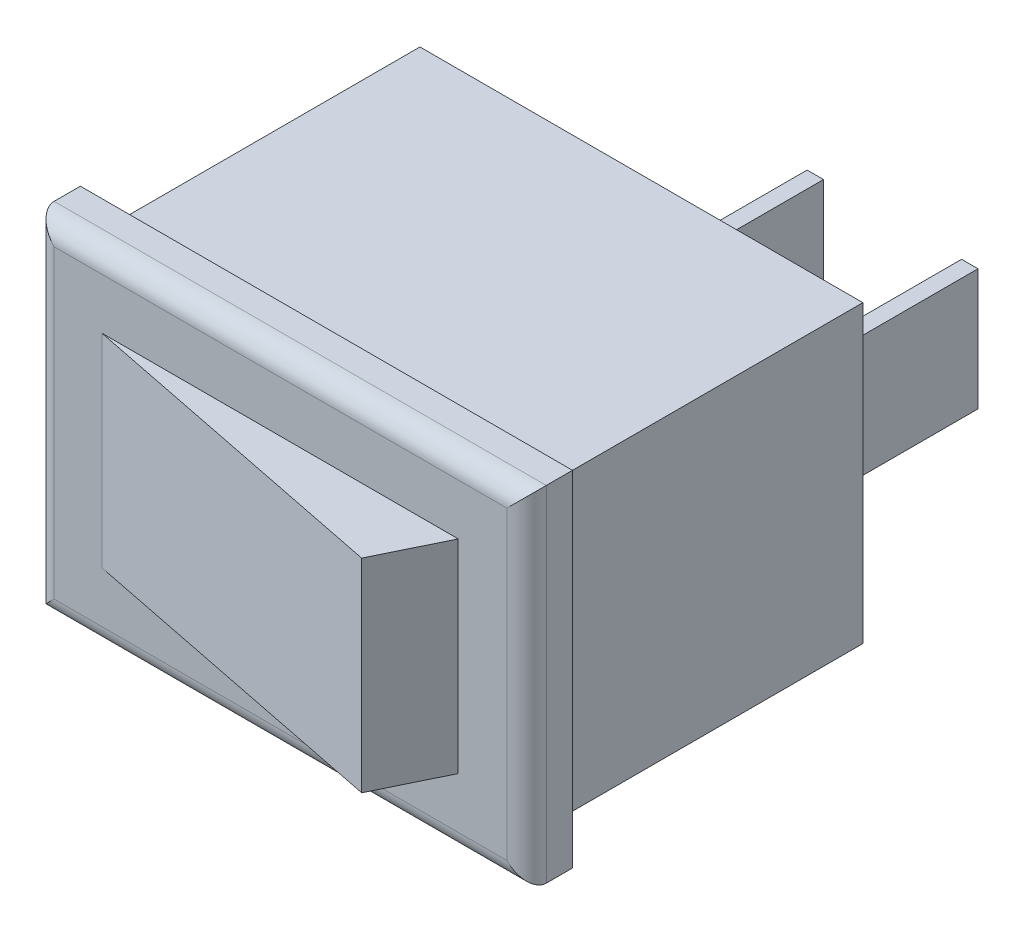
SolidWorks part; units mm, degrees
ref_plane "前视基准面" through (0, 0, 0) normal (0, 0, 1) x (1, 0, 0)
ref_plane "上视基准面" through (0, 0, 0) normal (0, 1, 0) x (1, 0, 0)
ref_plane "右视基准面" through (0, 0, 0) normal (1, 0, 0) x (0, 0, -1)
other "Configuration Table"
ref_plane "基准面1" through (0, 0, 11) normal (0, 0, 1) x (1, 0, 0)
sketch "草图1" plane through (0, 0, 11) normal (0, 0, 1) x (1, 0, 0)
  line L0 (-7.5, 5.25) -> (-7.5, -5.25)
  line L1 (-7.5, -5.25) -> (7.5, -5.25)
  line L2 (7.5, -5.25) -> (7.5, 5.25)
  line L3 (7.5, 5.25) -> (-7.5, 5.25)
extrude "凸台-拉伸1" add sketch "草图1" against normal blind 1.4
ref_plane "基准面2" through (0, -3.0974, 0) normal (0, -1, 0) x (1, 0, 0)
sketch "草图2" plane through (0, -3.0974, 0) normal (0, -1, 0) x (1, 0, 0)
  line L0 (5.4168, 11) -> (5.4168, 13.1716)
  line L1 (5.4168, 13.1716) -> (-5.4413, 11)
  line L2 (-5.4413, 11) -> (5.4168, 11)
extrude "凸台-拉伸2" add sketch "草图2" against normal blind 6.1948
sketch "草图3" plane through (0, 0, 9.6) normal (0, 0, -1) x (-1, 0, 0)
  line L0 (-6.75, -4.5) -> (-6.75, 4.5)
  line L1 (-6.75, 4.5) -> (6.75, 4.5)
  line L2 (6.75, 4.5) -> (6.75, -4.5)
  line L3 (6.75, -4.5) -> (-6.75, -4.5)
extrude "凸台-拉伸3" add sketch "草图3" along normal blind 9.6
sketch "草图4" plane through (0, 0, 0) normal (0, 0, -1) x (-1, 0, 0)
  line L0 (0.9153, 2.5) -> (0.9153, -2.5)
  line L1 (0.9153, -2.5) -> (-0.9153, -2.5)
  line L2 (-0.9153, -2.5) -> (-0.9153, 2.5)
  line L3 (-0.9153, 2.5) -> (0.9153, 2.5)
extrude "凸台-拉伸4" add sketch "草图4" along normal blind 0.3
sketch "草图5" plane through (0, 0, -0.3) normal (0, 0, -1) x (-1, 0, 0)
  line L0 (0.25, 1.85) -> (0.25, -1.85)
  line L1 (0.25, -1.85) -> (-0.25, -1.85)
  line L2 (-0.25, -1.85) -> (-0.25, 1.85)
  line L3 (-0.25, 1.85) -> (0.25, 1.85)
extrude "凸台-拉伸5" add sketch "草图5" along normal blind 5
sketch "草图6" plane through (0, 0, 0) normal (0, 0, -1) x (-1, 0, 0)
  line L0 (-3.7945, 2.5) -> (-3.7945, -2.5)
  line L1 (-3.7945, -2.5) -> (-5.625, -2.5)
  line L2 (-5.625, -2.5) -> (-5.625, 2.5)
  line L3 (-5.625, 2.5) -> (-3.7945, 2.5)
extrude "凸台-拉伸6" add sketch "草图6" along normal blind 0.3
sketch "草图7" plane through (0, 0, -0.3) normal (0, 0, -1) x (-1, 0, 0)
  line L0 (-4.9598, 1.85) -> (-4.4598, 1.85)
  line L1 (-4.4598, 1.85) -> (-4.4598, -1.85)
  line L2 (-4.4598, -1.85) -> (-4.9598, -1.85)
  line L3 (-4.9598, -1.85) -> (-4.9598, 1.85)
extrude "凸台-拉伸7" add sketch "草图7" along normal blind 5
draft "拔模1" type of draft neutral plane draft angle 26 faces to draft 1 face at (5.4168, 0, 12.0858) neutral plane through (0, 0, 11) neutral plane normal (0, 0, 1) parameters "D1"=26
fillet "圆角1" radius 0.6 4 edges at (7.5, 0, 11) (0, 5.25, 11) (0, -5.25, 11) (-7.5, 0, 11)
sketch "草图8" [suppressed] plane through (0, 0, 0) normal (0, 0, -1) x (-1, 0, 0)
  line L4 (-6.75, -4.5) -> (6.75, -4.5)
  line L5 (6.75, -4.5) -> (6.75, 4.5)
  line L6 (6.75, 4.5) -> (-6.75, 4.5)
  line L7 (-6.75, 4.5) -> (-6.75, -4.5)
  line L8 (-6.75, -4.5) -> (6.75, -4.5)
  line L9 (6.75, -4.5) -> (6.75, 4.5)
  line L10 (6.75, 4.5) -> (-6.75, 4.5)
  line L11 (-6.75, 4.5) -> (-6.75, -4.5)
  line L12 (7.5, 5.25) -> (-7.5, 5.25)
  line L13 (-7.5, 5.25) -> (-7.5, -5.25)
  line L14 (-7.5, -5.25) -> (7.5, -5.25)
  line L15 (7.5, -5.25) -> (7.5, 5.25)
  line L16 (7.5, 5.25) -> (-7.5, 5.25)
  line L17 (-7.5, 5.25) -> (-7.5, -5.25)
  line L18 (-7.5, -5.25) -> (7.5, -5.25)
  line L19 (7.5, -5.25) -> (7.5, 5.25)
  dimension "D1" = 0
  dimension "D2" = 0
